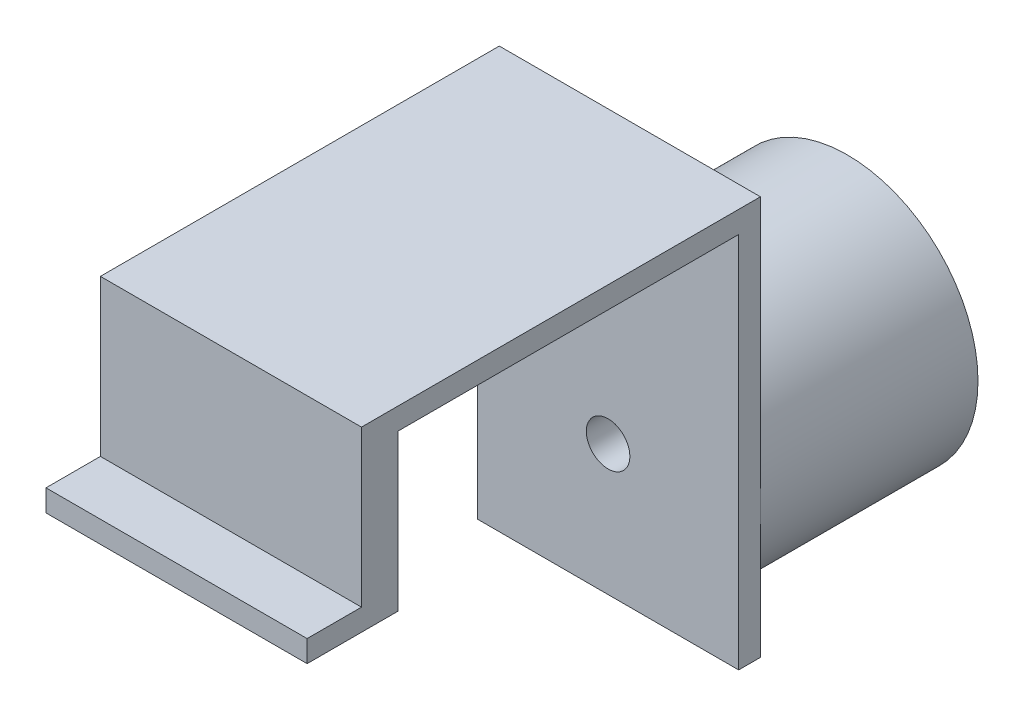
SolidWorks part; units mm, degrees
ref_plane "Front Plane" through (0, 0, 0) normal (0, 0, 1) x (1, 0, 0)
ref_plane "Top Plane" through (0, 0, 0) normal (0, 1, 0) x (1, 0, 0)
ref_plane "Right Plane" through (0, 0, 0) normal (1, 0, 0) x (0, 0, -1)
sketch "Sketch2" plane through (0, 0, 0) normal (0, 0, 1) x (1, 0, 0)
  circle A0 centre (0, 0) radius 18
extrude "Boss-Extrude1" add sketch "Sketch2" along normal blind 30
sketch "Sketch3" plane through (0, 0, 30) normal (0, 0, 1) x (1, 0, 0)
  circle A0 centre (0, 0) radius 3
  dimension "D1" = 0
sketch "Sketch4" plane through (0, 0, 30) normal (0, 0, 1) x (1, 0, 0)
  line L1 (-18, 37) -> (18, 37)
  line L2 (-18, 37) -> (-18, -18)
  line L3 (-18, -18) -> (18, -18)
  line L4 (18, 37) -> (18, -18)
  point P0 (0, 0)
  dimension "D1" = 36
  dimension "D2" = 55
  dimension "D3" = 18
extrude "Boss-Extrude2" add sketch "Sketch4" along normal blind 3
extrude "Cut-Extrude1" cut sketch "Sketch3" against normal blind 60 and the other way blind 3
sketch "Sketch6" plane through (0, 37, 0) normal (0, 1, 0) x (1, 0, 0)
  line L0 (-18, -33) -> (-18, -80)
  line L1 (-18, -80) -> (18, -80)
  line L2 (18, -80) -> (18, -33)
  line L3 (18, -33) -> (-18, -33)
  dimension "D1" = 47
extrude "Boss-Extrude3" add sketch "Sketch6" against normal blind 3
sketch "Sketch7" plane through (0, 0, 80) normal (0, 0, 1) x (1, 0, 0)
  line L1 (18, 34) -> (18, 12.5)
  line L2 (18, -18) -> (18, 34) construction
  line L3 (18, 12.5) -> (-18, 12.5)
  line L4 (-18, 34) -> (-18, -18) construction
  line L5 (-18, 12.5) -> (-18, 34)
  line L6 (-18, 37) -> (18, 37)
  line L7 (18, 37) -> (18, 34)
  line L8 (-18, 34) -> (-18, 37)
  dimension "D1" = 21.5
extrude "Boss-Extrude4" add sketch "Sketch7" along normal blind 5
sketch "Sketch8" plane through (0, 0, 85) normal (0, 0, 1) x (1, 0, 0)
  line L0 (-18, 12.5) -> (-18, 15.5)
  line L1 (-18, 37) -> (-18, 12.5) construction
  line L2 (-18, 15.5) -> (18, 15.5)
  line L3 (18, 12.5) -> (18, 37) construction
  line L4 (18, 15.5) -> (18, 12.5)
  line L5 (18, 12.5) -> (-18, 12.5)
  dimension "D1" = 3
extrude "Boss-Extrude5" add sketch "Sketch8" along normal blind 7.5
equation "\"7.5.00mm\"=20"
